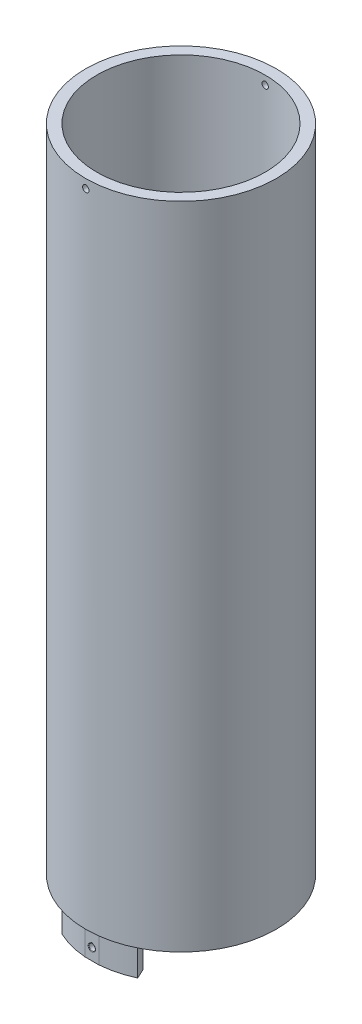
SolidWorks part; units mm, degrees
ref_plane "Front Plane" through (0, 0, 0) normal (0, 0, 1) x (1, 0, 0)
ref_plane "Top Plane" through (0, 0, 0) normal (0, 1, 0) x (1, 0, 0)
ref_plane "Right Plane" through (0, 0, 0) normal (1, 0, 0) x (0, 0, -1)
sketch "Sketch1" plane through (0, 0, 0) normal (0, 0, 1) x (1, 0, 0)
  line L0 (0, 16.072) -> (0, -6.4027) construction
  line L1 (-43.9039, 261.4935) -> (-38.8239, 261.4935)
  line L2 (-43.9039, 261.4935) -> (-43.9039, -38.2265)
  line L3 (-43.9039, -38.2265) -> (-38.8239, -38.2265)
  line L4 (-38.8239, 261.4935) -> (-38.8239, -38.2265)
  line L6 (-41.2369, -38.2265) -> (-36.1569, -38.2265)
  line L7 (-41.2369, -38.2265) -> (-41.2369, -52.1965)
  line L8 (-41.2369, -52.1965) -> (-36.1569, -52.1965)
  line L9 (-36.1569, -38.2265) -> (-36.1569, -52.1965)
  arc A0 (-36.1569, -38.2265) -> (-38.8239, -26.8964) centre (-61.5569, -38.2265) ccw
  dimension "D6" = 25.4
  dimension "D1" = 43.9039
  dimension "D2" = 5.08
  dimension "D3" = 299.72
  dimension "D4" = 13.97
  dimension "D5" = 5.08
revolve "Revolve1" add sketch "Sketch1" angle 360 about L0
sketch "Sketch2" plane through (0, 0, 0) normal (0, 0, 1) x (1, 0, 0)
  line L0 (0, -38.2265) -> (0, -46.8837)
  line L1 (-0.771, -45.621) -> (0, -45.1502)
  line L2 (0, -45.1502) -> (0.771, -45.621)
  line L3 (-41.2369, -38.2265) -> (41.2369, -38.2265) construction
  line L4 (-41.2369, -38.2265) -> (41.2369, -38.2265)
  arc A0 (-0.771, -45.621) -> (0.771, -45.621) centre (0, -46.8837) ccw
extrude "Cut-Extrude1" cut sketch "Sketch2" against normal through all both and the other way through all
sketch "Sketch3" plane through (0, -52.1965, 0) normal (0, -1, 0) x (1, 0, 0)
  line L0 (0, 0) -> (-17.4275, 37.3733)
  line L1 (0, 0) -> (0, 14.6666) construction
  line L2 (0, 0) -> (17.4275, 37.3733)
  line L3 (0, 0) -> (-17.4275, -37.3733)
  line L4 (0, 0) -> (17.4275, -37.3733)
  circle A0 centre (0, 0) radius 41.2369 construction
  circle A1 centre (0, 0) radius 41.2369 construction
  circle A2 centre (0, 0) radius 41.2369
  circle A3 centre (0, 0) radius 41.2369
  point P14 (-20.6185, -35.7122)
  dimension "D3" = 25
  dimension "D1" = 25
  dimension "D2" = 25
  dimension "D4" = 25
extrude "Cut-Extrude4" cut sketch "Sketch3" against normal up to surface (13.97 mm away) contours L3 A1 L0 A2 | A1 L4 A2 L2 up to face at (0, -38.2265, 41.2369)
sketch "Sketch4" plane through (0, -52.1965, 0) normal (0, -1, 0) x (1, 0, 0)
  line L0 (-3.2004, -41.2369) -> (3.2004, -41.2369)
  line L1 (-3.2004, -41.2369) -> (-3.2004, -37.2491)
  line L2 (-3.2004, -41.1125) -> (3.2004, -41.1125)
  circle A0 centre (0, 0) radius 41.2369
  point P6 (0, -41.2369)
  point P9 (0, 0)
  point P10 (0, 0)
  arc M5 (-17.4275, -37.3733) -> (17.4275, -37.3733) centre (0, 0) ccw
extrude "Cut-Extrude5" cut sketch "Sketch4" against normal up to surface (13.97 mm away) contours L2 M5 up to face at (0, -38.2265, 0)
pattern_circular "CirPattern1" count 2 every 180 of "Cut-Extrude5"
sketch "Sketch5" plane through (0, 0, 0) normal (0, 0, 1) x (1, 0, 0)
  line L0 (0, 261.4935) -> (0, 257.4295)
  line L1 (43.9039, 261.4935) -> (-43.9039, 261.4935) construction
  line L2 (-0.771, 258.6923) -> (0, 259.1631)
  line L3 (0, 259.1631) -> (0.771, 258.6923)
  arc A0 (-0.771, 258.6923) -> (0.771, 258.6923) centre (0, 257.4295) ccw
  dimension "D1" = 4.064
extrude "Cut-Extrude6" cut sketch "Sketch5" against normal through all both and the other way through all
fillet "Fillet1" radius 0.254 6 edges at (-0.3855, -45.3856, -41.1125) (0.3855, -45.3856, -41.1125) (0.3855, -45.3856, 41.1125) (-0.3855, -45.3856, 41.1125) (0, -48.3633, -41.1125) (0, -48.3633, 41.1125)
